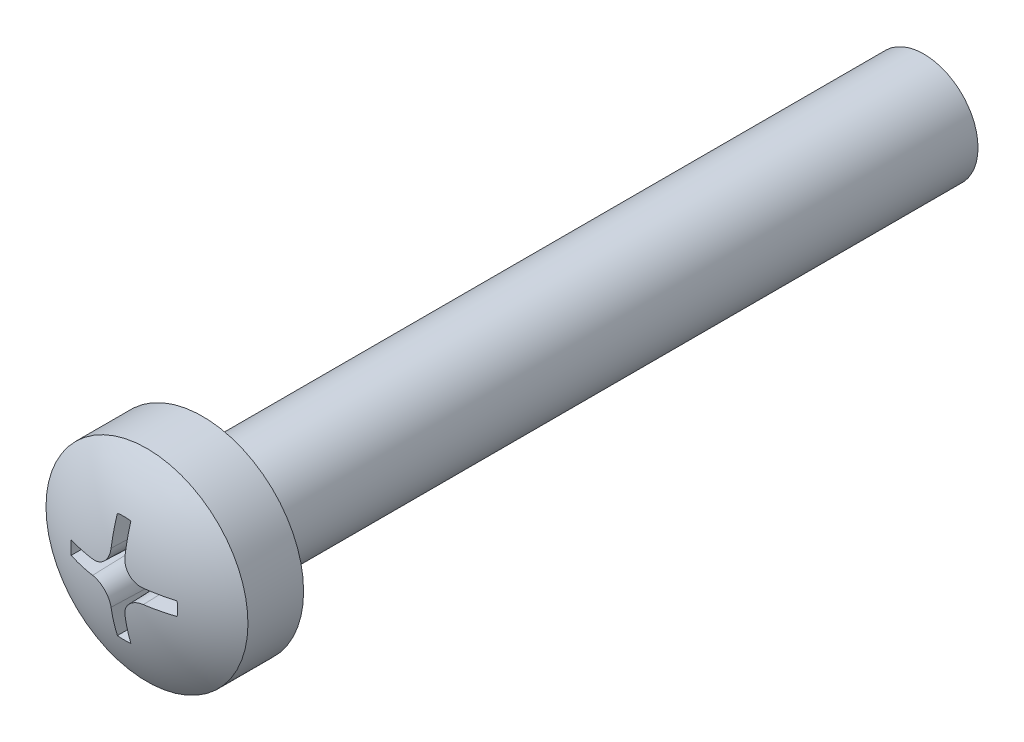
SolidWorks part; units mm, degrees
material "普通碳钢"
ref_plane "Plane1" through (0, 0, 0) normal (0, 0, 1) x (1, 0, 0)
ref_plane "Plane2" through (0, 0, 0) normal (0, 1, 0) x (1, 0, 0)
ref_plane "Plane3" through (0, 0, 0) normal (1, 0, 0) x (0, 0, -1)
sketch "Sketch1" plane through (0, 0, 0) normal (0, 0, 1) x (1, 0, 0)
  circle A0 centre (0, 0) radius 1.5
  dimension "D1" = 3
extrude "Base-Extrude" add sketch "Sketch1" along normal blind 20
sketch "Sketch6" plane through (0, 0, 0) normal (0, 1, 0) x (1, 0, 0)
  line L0 (0, 0.3936) -> (0, -34.4908) construction
  line L1 (0, -20) -> (0, 0) construction
  line L2 (0, -20) -> (2.8, -20)
  line L3 (2.8, -20) -> (2.8, -21.5425)
  line L4 (0, -22.4) -> (0, -20)
  line L5 (-1.5, -20) -> (1.5, -20) construction
  arc A0 (2.8, -21.5425) -> (0, -22.4) centre (0, -17.4) cw
  dimension "D1" = 2.4
  dimension "D9" = 5
  dimension "D8" = 2.8
revolve "Boss-Revolve2" add sketch "Sketch6" angle 360 about L0
ref_plane "Plane6" through (0, 0, 22.7) normal (0, 0, -1) x (-1, 0, 0)
sketch "Sketch7" plane through (0, 0, 22.7) normal (0, 0, -1) x (-1, 0, 0)
  line L0 (-7.1, 0) -> (5.9, 0) construction
  line L1 (0, 7.5) -> (0, -7) construction
  line L2 (0.205, 1.4859) -> (0.205, 0.7082)
  line L3 (0, 0) -> (4.9858, 4.9858) construction
  line L4 (1.4859, 0.205) -> (0.703, 0.2082)
  line L5 (1.4859, -0.205) -> (0.703, -0.2082)
  line L6 (0.205, -1.4859) -> (0.205, -0.7082)
  line L7 (-0.205, -1.4859) -> (-0.205, -0.7082)
  line L8 (-1.4859, -0.205) -> (-0.703, -0.2082)
  line L9 (-1.4859, 0.205) -> (-0.703, 0.2082)
  line L10 (-0.205, 1.4859) -> (-0.205, 0.7082)
  arc A0 (-0.205, 1.4859) -> (0.205, 1.4859) centre (0, 0) cw
  arc A1 (1.4859, -0.205) -> (1.4859, 0.205) centre (0, 0) ccw
  arc A2 (0.205, 0.7082) -> (0.703, 0.2082) centre (0.705, 0.7082) ccw
  arc A3 (-0.205, 0.7082) -> (-0.703, 0.2082) centre (-0.705, 0.7082) cw
  arc A4 (-0.205, -1.4859) -> (0.205, -1.4859) centre (0, 0) ccw
  arc A5 (-0.205, -0.7082) -> (-0.703, -0.2082) centre (-0.705, -0.7082) ccw
  arc A6 (-1.4859, -0.205) -> (-1.4859, 0.205) centre (0, 0) cw
  arc A7 (0.703, -0.2082) -> (0.205, -0.7082) centre (0.705, -0.7082) ccw
  dimension "D1" = 0.5
  dimension "D10" = 1.5
  dimension "D11" = 0.41
extrude "Cut-Extrude1" cut sketch "Sketch7" along normal blind 1.8 draft 2
